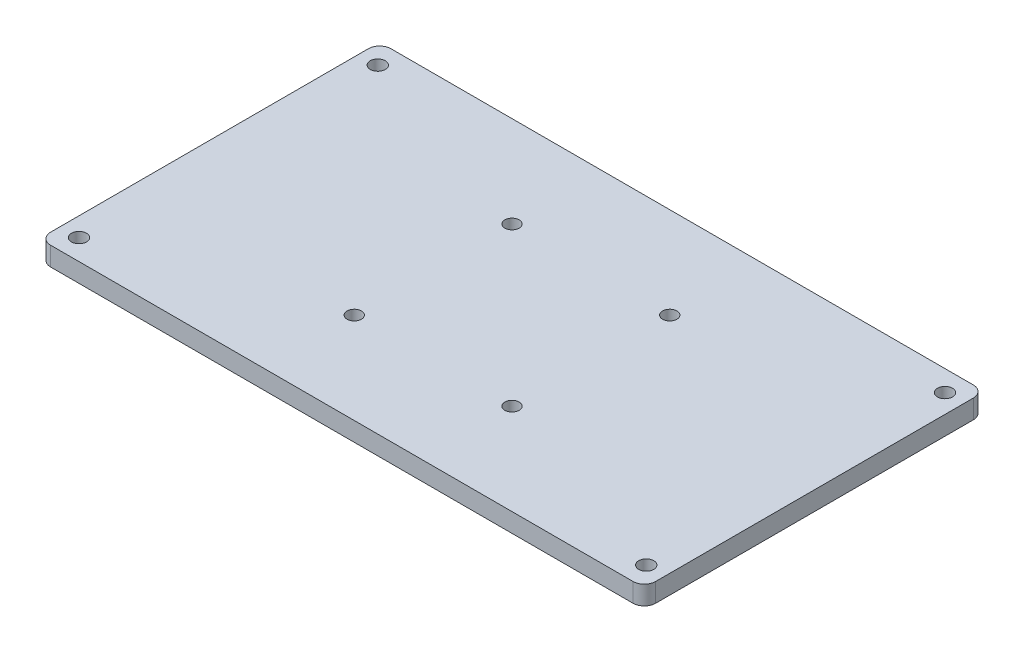
SolidWorks part; units mm, degrees
ref_plane "Спереди" through (0, 0, 0) normal (0, 0, 1) x (1, 0, 0)
ref_plane "Сверху" through (0, 0, 0) normal (0, 1, 0) x (1, 0, 0)
ref_plane "Справа" through (0, 0, 0) normal (1, 0, 0) x (0, 0, -1)
sketch "Эскиз1" plane through (0, 0, 0) normal (0, 1, 0) x (1, 0, 0)
  line L0 (0, 0) -> (36.9242, 36.9242) construction
  line L1 (-80, -45) -> (80, -45)
  line L2 (-80, -45) -> (-80, 45)
  line L3 (-80, 45) -> (80, 45)
  line L4 (80, -45) -> (80, 45)
  line L5 (0, 45) -> (0, -45) construction
  line L6 (-80, 0) -> (80, 0) construction
  line L8 (-75, -39.5) -> (75, -39.5) construction
  line L9 (-75, -39.5) -> (-75, 39.5) construction
  line L10 (-75, 39.5) -> (75, 39.5) construction
  line L11 (75, -39.5) -> (75, 39.5) construction
  line L12 (0, 39.5) -> (0, -39.5) construction
  line L13 (-75, 0) -> (75, 0) construction
  circle A0 centre (0, 0) radius 29.5 construction
  circle A1 centre (20.8597, 20.8597) radius 1.9
  circle A2 centre (20.8597, -20.8597) radius 1.9
  circle A3 centre (-20.8597, -20.8597) radius 1.9
  circle A4 centre (-20.8597, 20.8597) radius 1.9
  circle A5 centre (-75, 39.5) radius 2
  circle A6 centre (75, 39.5) radius 2
  circle A7 centre (75, -39.5) radius 2
  circle A8 centre (-75, -39.5) radius 2
  point P0 (0, 0)
  point P18 (0, 0)
  dimension "D3" = 45
  dimension "D4" = 3.8
  dimension "D5" = 59
  dimension "D8" = 4
  dimension "D1" = 90
  dimension "D2" = 160
  dimension "D6" = 150
  dimension "D7" = 79
extrude "Бобышка-Вытянуть1" add sketch "Эскиз1" along normal blind 5
fillet "Скругление5" radius 3 4 edges at (-80, 2.5, -45) (80, 2.5, -45) (-80, 2.5, 45) (80, 2.5, 45)
